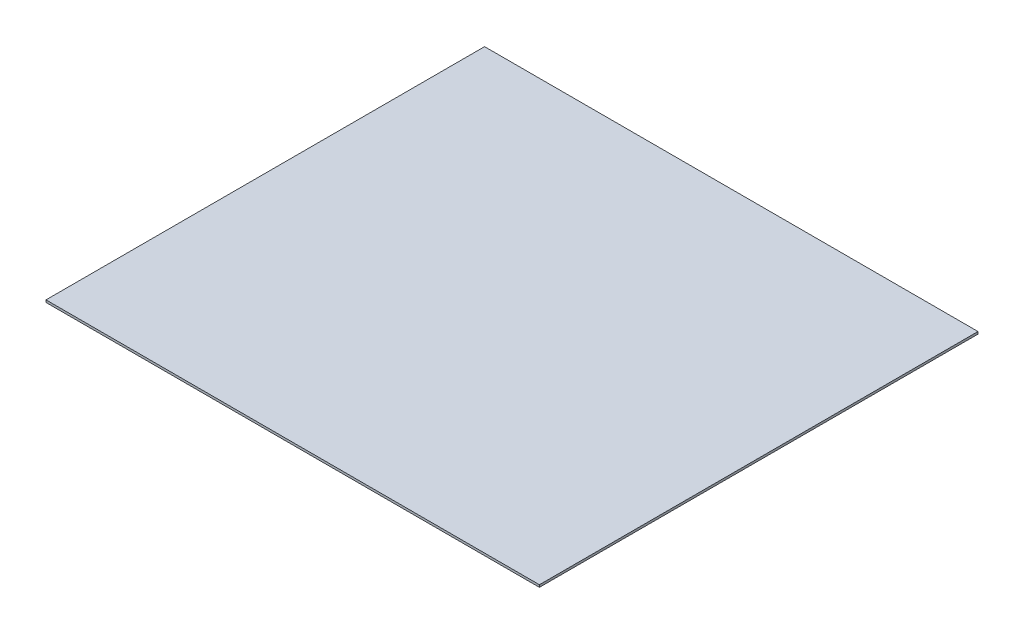
SolidWorks part; units mm, degrees
material "Acrylic (Medium-high impact)"
ref_plane "Front Plane" through (0, 0, 0) normal (0, 0, 1) x (1, 0, 0)
ref_plane "Top Plane" through (0, 0, 0) normal (0, 1, 0) x (1, 0, 0)
ref_plane "Right Plane" through (0, 0, 0) normal (1, 0, 0) x (0, 0, -1)
sketch "Sketch1" plane through (0, 0, 0) normal (0, 1, 0) x (1, 0, 0)
  line L1 (-342.9, -292.6534) -> (342.9, -292.6534)
  line L2 (-342.9, -292.6534) -> (-342.9, 316.9466)
  line L3 (-342.9, 316.9466) -> (342.9, 316.9466)
  line L4 (342.9, -292.6534) -> (342.9, 316.9466)
  dimension "D1" = 685.8
  dimension "D2" = 609.6
extrude "Boss-Extrude1" add sketch "Sketch1" along normal blind 3.175 contours L3 L4 L1 L2
sketch "Sketch2" plane through (0, 3.175, 0) normal (0, 1, 0) x (1, 0, 0)
  line L0 (-171.45, 228.6) -> (-171.45, -228.6)
  line L1 (-228.6, -228.6) -> (228.6, -228.6)
  line L2 (-228.6, -228.6) -> (-228.6, 228.6)
  line L3 (-228.6, 228.6) -> (228.6, 228.6)
  line L4 (228.6, -228.6) -> (228.6, 228.6)
  line L5 (-114.3, 228.6) -> (-114.3, -228.6)
  line L6 (0, 228.6) -> (0, -228.6)
  line L7 (-57.15, 228.6) -> (-57.15, -228.6)
  line L8 (-228.6, 0) -> (228.6, 0)
  line L9 (228.6, 171.45) -> (-228.6, 171.45)
  line L10 (-228.6, 114.3) -> (228.6, 114.3)
  line L11 (-228.6, 57.15) -> (228.6, 57.15)
  line L12 (171.45, 228.6) -> (171.45, -228.6)
  line L13 (114.3, 228.6) -> (114.3, -228.6)
  line L14 (57.15, 228.6) -> (57.15, -228.6)
  line L15 (-228.6, -57.15) -> (228.6, -57.15)
  line L16 (-228.6, -114.3) -> (228.6, -114.3)
  line L17 (228.6, -171.45) -> (-228.6, -171.45)
  point P0 (0, 0)
  dimension "D1" = 457.2
  dimension "D2" = 457.2
  dimension "D3" = 57.15
  dimension "D4" = 57.15
  dimension "D5" = 57.15
  dimension "D6" = 57.15
  dimension "D7" = 57.15
  dimension "D8" = 57.15
